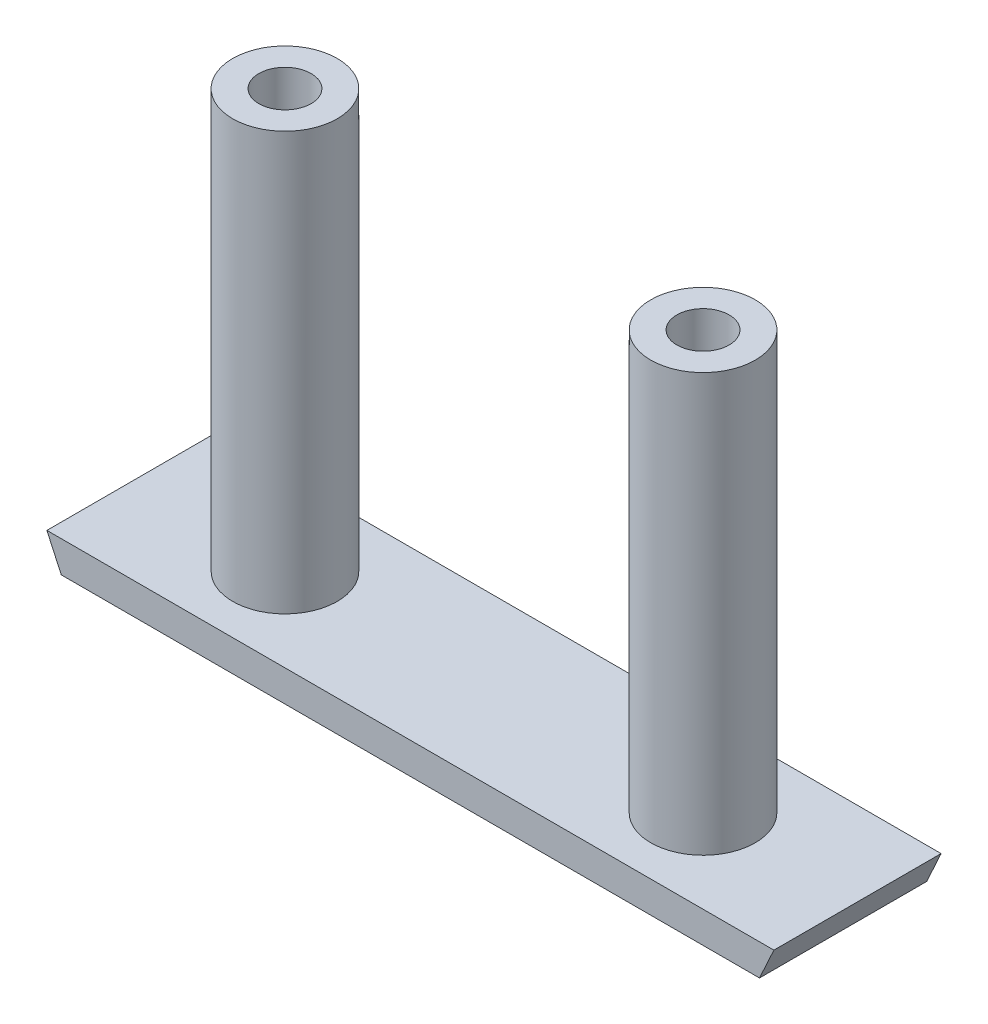
SolidWorks part; units mm, degrees
ref_plane "Front Plane" through (0, 0, 0) normal (0, 0, 1) x (1, 0, 0)
ref_plane "Top Plane" through (0, 0, 0) normal (0, 1, 0) x (1, 0, 0)
ref_plane "Right Plane" through (0, 0, 0) normal (1, 0, 0) x (0, 0, -1)
sketch "Sketch1" plane through (0, 0, 0) normal (0, 0, 1) x (1, 0, 0)
  line L0 (-44.173, -17.9705) -> (44.173, -17.9705)
  line L1 (-42.4241, -21.7805) -> (42.4241, -21.7805)
  line L2 (-44.173, -17.9705) -> (-42.4241, -21.7805)
  line L3 (44.173, -17.9705) -> (42.4241, -21.7805)
  circle A0 centre (0, 0) radius 47.6885 construction
  point P7 (0, -47.6885)
  dimension "D1" = 95.377
  dimension "D2" = 3.81
  dimension "D3" = 25.908
extrude "Boss-Extrude1" add sketch "Sketch1" along normal blind 20.32
sketch "Sketch2" plane through (0, -17.9705, 0) normal (0, 1, 0) x (1, 0, 0)
  line L0 (44.173, -20.32) -> (-44.173, -20.32) construction
  line L1 (0, -20.32) -> (0, 0) construction
  circle A0 centre (-25.4, -10.16) radius 3.175
  circle A1 centre (25.4, -10.16) radius 3.175
  circle A3 centre (-25.4, -10.16) radius 6.35
  circle A4 centre (25.4, -10.16) radius 6.35
  dimension "D1" = 6.35
  dimension "D6" = 12.7
  dimension "D7" = 12.7
  dimension "D2" = 10.16
  dimension "D3" = 25.4
  dimension "D4" = 25.4
extrude "Boss-Extrude2" add sketch "Sketch2" along normal blind 50.8
